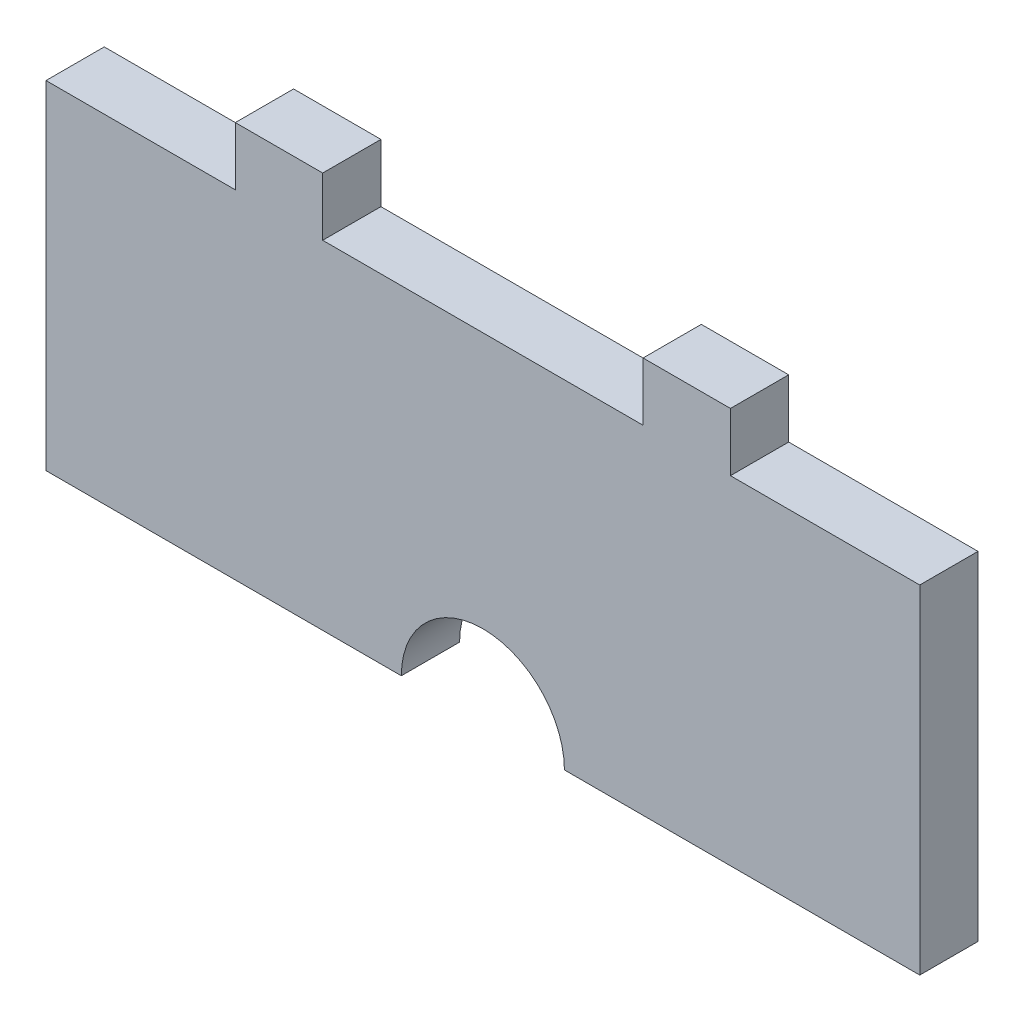
SolidWorks part; units mm, degrees
material "Acrylic (Medium-high impact)"
ref_plane "Front Plane" through (0, 0, 0) normal (0, 0, 1) x (1, 0, 0)
ref_plane "Top Plane" through (0, 0, 0) normal (0, 1, 0) x (1, 0, 0)
ref_plane "Right Plane" through (0, 0, 0) normal (1, 0, 0) x (0, 0, -1)
sketch "Sketch1" plane through (0, 0, 0) normal (0, 0, 1) x (1, 0, 0)
  line L0 (-76.2, 142.24) -> (-6.35, 142.24) construction
  line L1 (-76.2, 215.9) -> (-34.925, 215.9)
  line L2 (-76.2, 215.9) -> (-76.2, 142.24)
  line L3 (-76.2, 142.24) -> (-76.2, 215.9) construction
  line L4 (114.3, 215.9) -> (114.3, 142.24)
  line L10 (53.975, 215.9) -> (53.975, 228.6) construction
  line L11 (73.025, 228.6) -> (53.975, 228.6) construction
  line L12 (73.025, 215.9) -> (73.025, 228.6) construction
  line L13 (-15.875, 215.9) -> (-15.875, 228.6) construction
  line L14 (-15.875, 228.6) -> (-34.925, 228.6) construction
  line L15 (-34.925, 215.9) -> (-34.925, 228.6) construction
  line L16 (-15.875, 215.9) -> (53.975, 215.9)
  line L17 (73.025, 215.9) -> (114.3, 215.9)
  line L18 (-76.2, 142.24) -> (114.3, 142.24)
  line L19 (53.975, 215.9) -> (53.975, 228.6)
  line L20 (73.025, 228.6) -> (53.975, 228.6)
  line L21 (73.025, 215.9) -> (73.025, 228.6)
  line L22 (-15.875, 215.9) -> (-15.875, 228.6)
  line L23 (-15.875, 228.6) -> (-34.925, 228.6)
  line L24 (-34.925, 215.9) -> (-34.925, 228.6)
extrude "Extrude1" add sketch "Sketch1" against normal blind 12.7
sketch "Sketch2" plane through (0, 0, 0) normal (0, 0, 1) x (1, 0, 0)
  arc A1 (36.83, 142.24) -> (1.27, 142.24) centre (19.05, 142.24) ccw construction
  circle A3 centre (19.05, 142.24) radius 17.78
extrude "Cut-Extrude1" cut sketch "Sketch2" against normal through all
